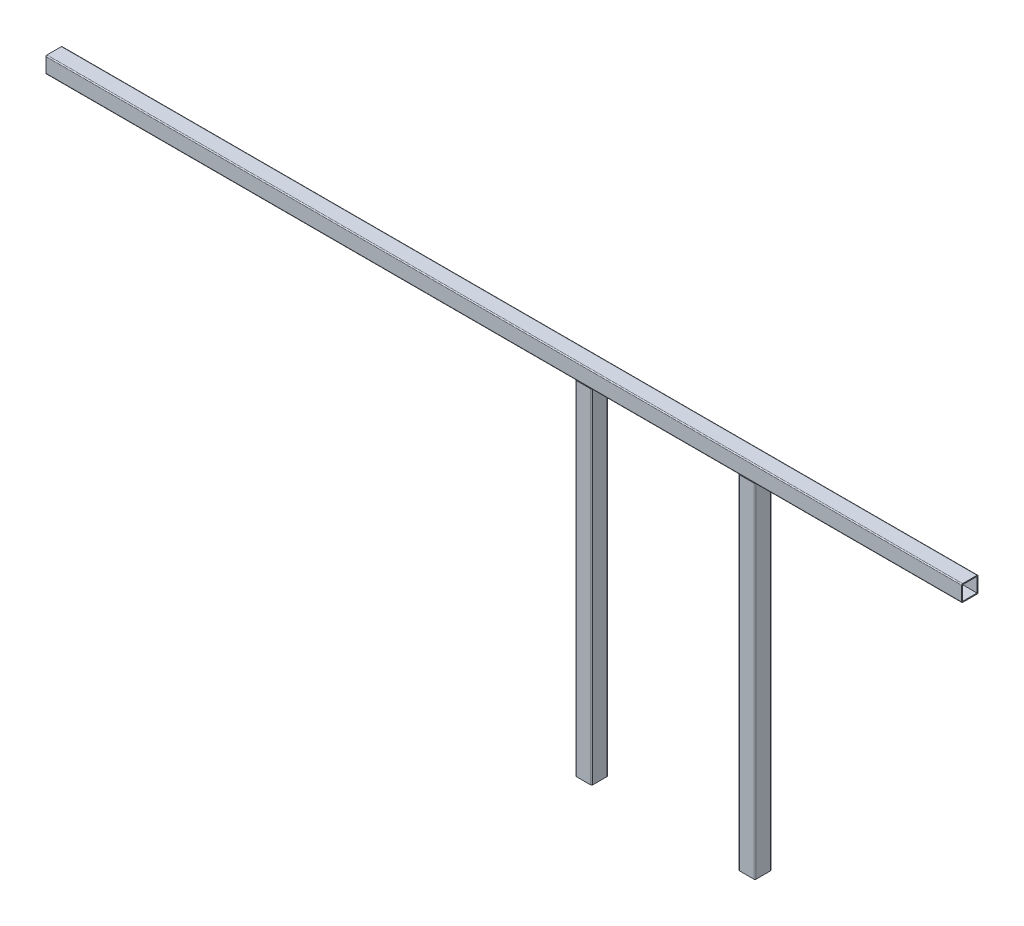
SolidWorks part; units mm, degrees
material "Простая углеродистая сталь"
ref_plane "Спереди" through (0, 0, 0) normal (0, 0, 1) x (1, 0, 0)
ref_plane "Сверху" through (0, 0, 0) normal (0, 1, 0) x (1, 0, 0)
ref_plane "Справа" through (0, 0, 0) normal (1, 0, 0) x (0, 0, -1)
sketch "Эскиз1" plane through (0, 0, 0) normal (0, 0, 1) x (1, 0, 0)
  line L0 (0, 0) -> (5605, 0)
  line L1 (3290, 0) -> (3290, -2150)
  line L3 (4290, 0) -> (4290, -2150)
  dimension "D1" = 5605
  dimension "D2" = 2150
  dimension "D3" = 1000
  dimension "D4" = 3290
other "Квадратная труба гост 8639-82 100 X 100 X 6.0(1)"
ref_plane "Плоскость1" through (0, 0, 0) normal (1, 0, 0) x (0, 1, 0)
sketch "Sketch1" plane through (0, 0, 0) normal (1, 0, 0) x (0, 1, 0)
  line L0 (-43.999, -44) -> (43.999, -44)
  line L1 (-44, -43.999) -> (-44, 43.999)
  line L2 (43.999, 44) -> (-43.999, 44)
  line L3 (44, 43.999) -> (44, -43.999)
  line L4 (-43.999, -50) -> (43.999, -50)
  line L5 (-50, -43.999) -> (-50, 43.999)
  line L6 (43.999, 50) -> (-43.999, 50)
  line L7 (50, 43.999) -> (50, -43.999)
  arc A0 (50, 43.999) -> (43.999, 50) centre (43.999, 43.999) ccw
  arc A1 (43.999, -50) -> (50, -43.999) centre (43.999, -43.999) ccw
  arc A2 (-50, -43.999) -> (-43.999, -50) centre (-43.999, -43.999) ccw
  arc A3 (-43.999, 50) -> (-50, 43.999) centre (-43.999, 43.999) ccw
  arc A4 (-43.999, 44) -> (-44, 43.999) centre (-43.999, 43.999) ccw
  arc A5 (44, 43.999) -> (43.999, 44) centre (43.999, 43.999) ccw
  arc A6 (43.999, -44) -> (44, -43.999) centre (43.999, -43.999) ccw
  arc A7 (-44, -43.999) -> (-43.999, -44) centre (-43.999, -43.999) ccw
  point P0 (-50, 0)
  point P1 (50, 0)
  point P2 (0, 50)
  point P3 (0, -50)
  point P4 (0, 0)
  point P5 (-50, -50)
  point P6 (50, -50)
  point P7 (50, 50)
  point P8 (-50, 50)
  point P33 (0, 0)
  dimension "D1" = 6.001
  dimension "Thickness" = 6
  dimension "V_leg" = 100
equation "\"D1@Sketch1\" = \"Thickness@Sketch1\"+0.001"
